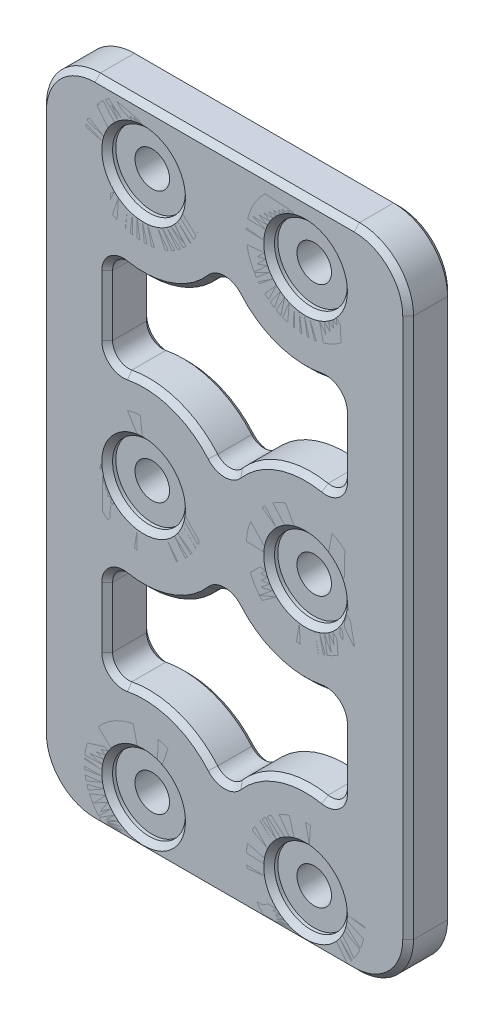
SolidWorks part; units mm, degrees
other "dystnas"
ref_plane "Front Plane" through (0, 0, 0) normal (0, 0, 1) x (1, 0, 0)
ref_plane "Top Plane" through (0, 0, 0) normal (0, 1, 0) x (1, 0, 0)
ref_plane "Right Plane" through (0, 0, 0) normal (1, 0, 0) x (0, 0, -1)
sketch "Sketch1" plane through (0, 0, 0) normal (0, 0, 1) x (1, 0, 0)
  line L0 (-49, 8.8083) -> (-19, 8.8083) construction
  line L1 (0, 0) -> (-68, 0)
  line L2 (0, 0) -> (0, 120)
  line L3 (0, 120) -> (-68, 120)
  line L4 (-68, 0) -> (-68, 120)
  line L5 (-34, 8.8083) -> (-34, 0) construction
  circle A0 centre (-49, 108.8083) radius 5.5 construction
  circle A1 centre (-49, 108.8083) radius 8.5 construction
  circle A2 centre (-49, 8.8083) radius 3.2
  circle A3 centre (-19, 8.8083) radius 3.2
  circle A4 centre (-19, 58.8083) radius 3.2
  circle A5 centre (-19, 108.8083) radius 3.2
  circle A6 centre (-49, 58.8083) radius 3.2
  circle A7 centre (-49, 108.8083) radius 3.2
  point P4 (-49, 8.8083)
  point P9 (-19, 8.8083)
  point P10 (-19, 58.8083)
  point P11 (-19, 108.8083)
  point P12 (-49, 58.8083)
  point P13 (-49, 108.8083)
  dimension "D7" = 11
  dimension "D10" = 2
  dimension "D12" = 6.4
  dimension "D1" = 68
  dimension "D2" = 2
  dimension "D4" = 30
  dimension "D5" = 50
  dimension "D6" = 100
  dimension "D9" = 120
  dimension "D8" = 3
  dimension "D3" = 3
  dimension "D11" = 3
extrude "Boss-Extrude1" add sketch "Sketch1" along normal blind 8.3
sketch "Sketch2" plane through (0, 0, 8.3) normal (0, 0, 1) x (1, 0, 0)
  circle A0 centre (-49, 8.8083) radius 6.75
  circle A1 centre (-19, 8.8083) radius 6.75
  circle A2 centre (-19, 58.8083) radius 6.75
  circle A3 centre (-19, 108.8083) radius 6.75
  circle A4 centre (-49, 58.8083) radius 6.75
  circle A5 centre (-49, 108.8083) radius 6.75
  dimension "D1" = 13.5
  dimension "D2" = 2
  dimension "D3" = 3
extrude "Cut-Extrude1" cut sketch "Sketch2" against normal blind 1.6
fillet "Fillet1" radius 10 4 edges at (0, 120, 4.15) (0, 0, 4.15) (-68, 0, 4.15) (-68, 120, 4.15)
sketch "Sketch3" plane through (0, 0, 8.3) normal (0, 0, 1) x (1, 0, 0)
  line L1 (-55.75, 108.8083) -> (-12.25, 108.8083)
  line L2 (-55.75, 108.8083) -> (-55.75, 8.8083)
  line L3 (-55.75, 8.8083) -> (-12.25, 8.8083)
  line L4 (-12.25, 108.8083) -> (-12.25, 8.8083)
  circle A0 centre (-19, 8.8083) radius 6.75 construction
  circle A1 centre (-49, 8.8083) radius 6.75 construction
  circle A2 centre (-49, 58.8083) radius 6.75 construction
  circle A3 centre (-19, 58.8083) radius 6.75 construction
  circle A4 centre (-19, 108.8083) radius 6.75 construction
  circle A5 centre (-49, 108.8083) radius 6.75 construction
  circle A6 centre (-19, 8.8083) radius 6.75 construction
  circle A7 centre (-49, 8.8083) radius 6.75 construction
  circle A8 centre (-49, 58.8083) radius 6.75 construction
  circle A9 centre (-19, 58.8083) radius 6.75 construction
  circle A10 centre (-19, 108.8083) radius 6.75 construction
  circle A11 centre (-49, 108.8083) radius 6.75 construction
  circle A12 centre (-19, 8.8083) radius 16.75
  circle A13 centre (-49, 8.8083) radius 16.75
  circle A14 centre (-49, 58.8083) radius 16.75
  circle A15 centre (-19, 58.8083) radius 16.75
  circle A16 centre (-19, 108.8083) radius 16.75
  circle A17 centre (-49, 108.8083) radius 16.75
  dimension "D1" = 10
extrude "Cut-Extrude3" cut sketch "Sketch3" against normal through all contours A17 L2 A14 A15 L4 A16 | A15 A14 L2 A13 A12 L4
fillet "Fillet2" radius 3 12 edges at (-55.75, 24.138, 4.15) (-55.75, 74.138, 4.15) (-55.75, 43.4786, 4.15) (-12.25, 24.138, 4.15) (-12.25, 74.138, 4.15) (-12.25, 43.4786, 4.15) (-12.25, 93.4786, 4.15) (-55.75, 93.4786, 4.15) (-34, 66.2623, 4.15) (-34, 51.3543, 4.15) (-34, 16.2623, 4.15) (-34, 101.3543, 4.15)
chamfer "Chamfer1" distance 1 angle 45 76 edges at (-34, 98.9606, 0) (-24.5188, 92.9936, 0) (-13.3407, 91.7315, 0) (-12.25, 83.8083, 0) (-13.3407, 75.885, 0) (-24.5188, 74.623, 0) (-34, 68.656, 0) (-43.4812, 74.623, 0) (-54.6593, 75.885, 0) (-55.75, 83.8083, 0) (-54.6593, 91.7315, 0) (-43.4812, 92.9936, 0) (-45.8, 108.8083, 0) (-45.8, 58.8083, 0) (-15.8, 108.8083, 0) (-15.8, 58.8083, 0) (-15.8, 8.8083, 0) (-45.8, 8.8083, 0) (-65.0711, 117.0711, 0) (-68, 60, 0) (-65.0711, 2.9289, 0) (-34, 0, 0) (-2.9289, 2.9289, 0) (0, 60, 0) (-2.9289, 117.0711, 0) (-34, 120, 0) (-13.3407, 41.7315, 0) (-12.25, 33.8083, 0) (-13.3407, 25.885, 0) (-24.5188, 24.623, 0) (-34, 18.656, 0) (-43.4812, 24.623, 0) (-54.6593, 25.885, 0) (-55.75, 33.8083, 0) (-54.6593, 41.7315, 0) (-43.4812, 42.9936, 0) (-34, 48.9606, 0) (-24.5188, 42.9936, 0) (-54.6593, 75.885, 8.3) (-43.4812, 74.623, 8.3) (-34, 68.656, 8.3) (-24.5188, 74.623, 8.3) (-13.3407, 75.885, 8.3) (-12.25, 83.8083, 8.3) (-13.3407, 91.7315, 8.3) (-24.5188, 92.9936, 8.3) (-34, 98.9606, 8.3) (-43.4812, 92.9936, 8.3) (-54.6593, 91.7315, 8.3) (-55.75, 83.8083, 8.3) (-54.6593, 25.885, 8.3) (-43.4812, 24.623, 8.3) (-34, 18.656, 8.3) (-24.5188, 24.623, 8.3) (-13.3407, 25.885, 8.3) (-12.25, 33.8083, 8.3) (-13.3407, 41.7315, 8.3) (-24.5188, 42.9936, 8.3) (-34, 48.9606, 8.3) (-43.4812, 42.9936, 8.3) (-54.6593, 41.7315, 8.3) (-55.75, 33.8083, 8.3) (-2.9289, 2.9289, 8.3) (-34, 0, 8.3) (-65.0711, 2.9289, 8.3) (-68, 60, 8.3) (-65.0711, 117.0711, 8.3) (-34, 120, 8.3) (-2.9289, 117.0711, 8.3) (0, 60, 8.3) (-42.25, 8.8083, 8.3) (-42.25, 108.8083, 8.3) (-12.25, 8.8083, 8.3) (-12.25, 58.8083, 8.3) (-12.25, 108.8083, 8.3) (-42.25, 58.8083, 8.3)
sketch "Sketch4" plane through (0, 0, 8.3) normal (0, 0, 1) x (1, 0, 0)
  circle A0 centre (-49, 108.8083) radius 11
  circle A1 centre (-19, 108.8083) radius 11
  circle A2 centre (-19, 58.8083) radius 11
  circle A3 centre (-19, 8.8083) radius 11
  circle A4 centre (-49, 58.8083) radius 11
  circle A5 centre (-49, 8.8083) radius 11
  circle A6 centre (-49, 108.8083) radius 7.75
  circle A7 centre (-19, 108.8083) radius 7.75
  circle A8 centre (-19, 58.8083) radius 7.75
  circle A9 centre (-19, 8.8083) radius 7.75
  circle A10 centre (-49, 58.8083) radius 7.75
  circle A11 centre (-49, 8.8083) radius 7.75
  line M69 (-58, 1) -> (-10, 1)
  line M73 (-10, 119) -> (-58, 119)
  circle M77 centre (-49, 8.8083) radius 7.75
  circle M78 centre (-49, 108.8083) radius 7.75
  circle M79 centre (-19, 8.8083) radius 7.75
  circle M80 centre (-19, 58.8083) radius 7.75
  circle M81 centre (-19, 108.8083) radius 7.75
  circle M82 centre (-49, 58.8083) radius 7.75
  dimension "D1" = 22
  dimension "D4" = 2
  dimension "D2" = 2
  dimension "D3" = 3
  dimension "D5" = 3
extrude "Boss-Extrude2" add sketch "Sketch4" against normal up to surface (8.3 mm away) separate body contours A0 M73 M78 | A1 M73 M81 | A4 M82 | A2 M80 | A3 M69 M79 | A5 M69 M77 up to face at (-34, 83.8083, 0)
